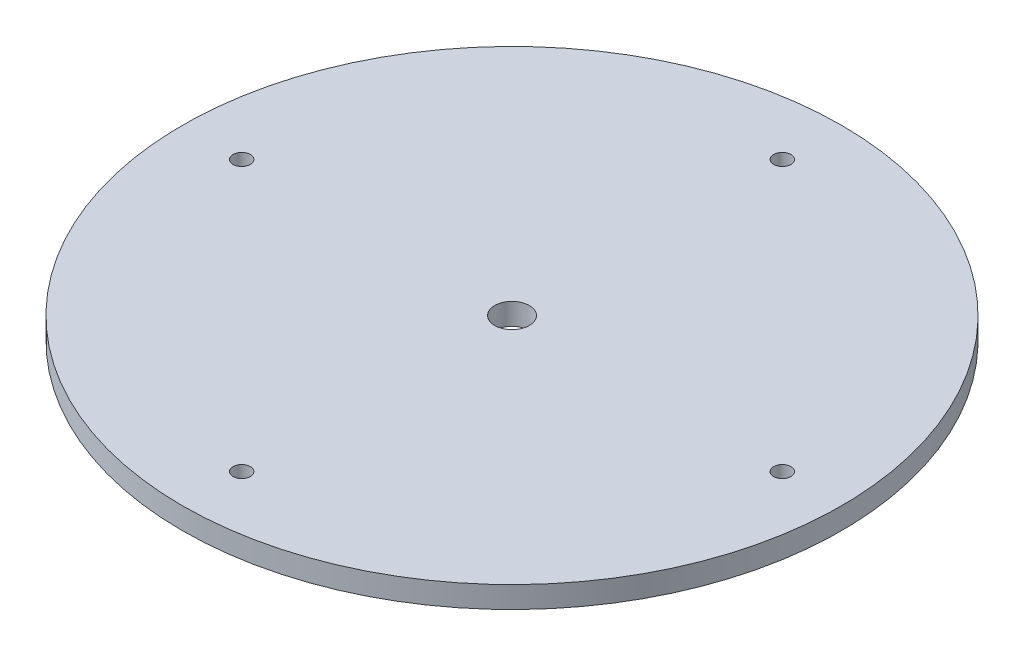
SolidWorks part; units mm, degrees
material "1060 Alloy"
ref_plane "Front Plane" through (0, 0, 0) normal (0, 0, 1) x (1, 0, 0)
ref_plane "Top Plane" through (0, 0, 0) normal (0, 1, 0) x (1, 0, 0)
ref_plane "Right Plane" through (0, 0, 0) normal (1, 0, 0) x (0, 0, -1)
sketch "Sketch1" plane through (0, 0, 0) normal (0, 1, 0) x (1, 0, 0)
  circle A0 centre (0, 0) radius 76.2
  circle A1 centre (0, 0) radius 4
  dimension "D1" = 152.4
  dimension "D2" = 8
extrude "Boss-Extrude2" add sketch "Sketch1" along normal blind 5 contours A0 A1
sketch "Sketch2" plane through (0, 5, 0) normal (0, 1, 0) x (1, 0, 0)
  circle A0 centre (0, 0) radius 62.5 construction
  circle A1 centre (0, -62.5) radius 2
  circle A2 centre (-62.5, 0) radius 2
  circle A3 centre (0, 62.5) radius 2
  circle A4 centre (62.5, 0) radius 2
  point P14 (0, 0)
  dimension "D1" = 125
  dimension "D2" = 4
  dimension "D3" = 4
extrude "Cut-Extrude1" cut sketch "Sketch2" against normal through all
